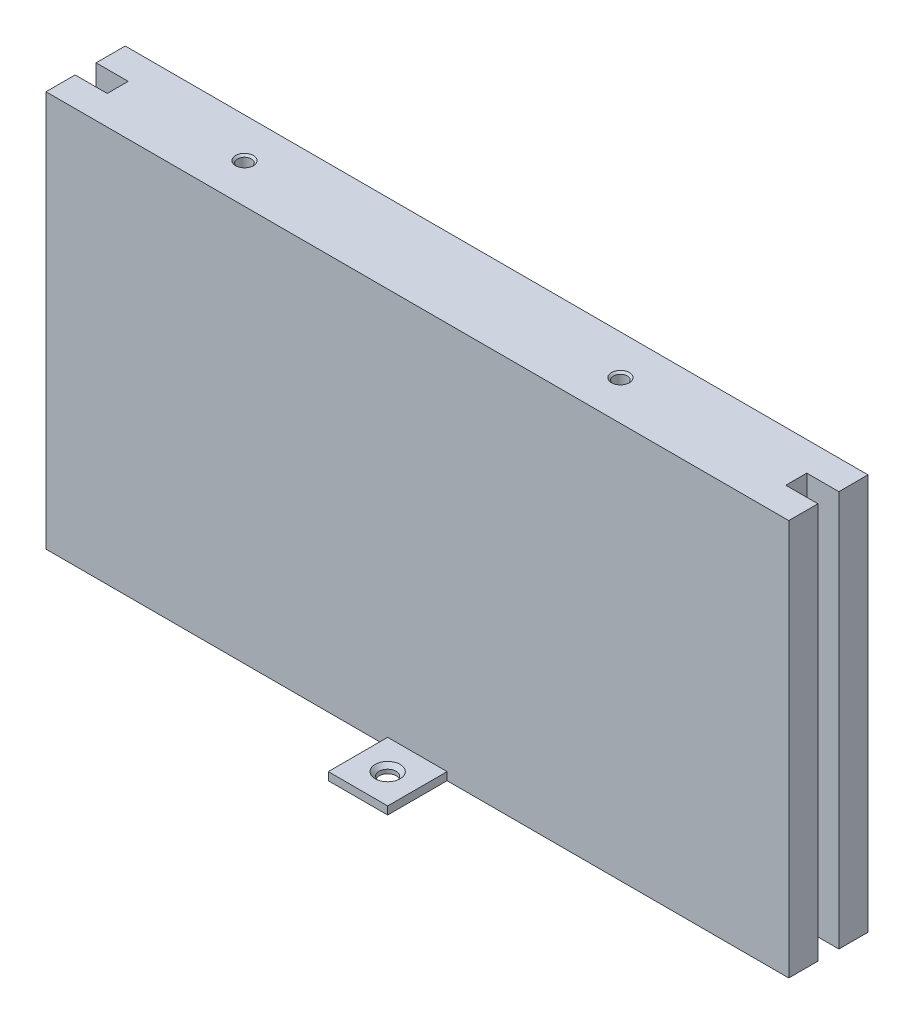
SolidWorks part; units mm, degrees
ref_plane "Front Plane" through (0, 0, 0) normal (0, 0, 1) x (1, 0, 0)
ref_plane "Top Plane" through (0, 0, 0) normal (0, 1, 0) x (1, 0, 0)
ref_plane "Right Plane" through (0, 0, 0) normal (1, 0, 0) x (0, 0, -1)
sketch "Sketch1" plane through (0, 0, 0) normal (0, 1, 0) x (1, 0, 0)
  line L0 (0, 0) -> (0, 20)
  line L1 (0, 20) -> (187.5, 20)
  line L2 (187.5, 20) -> (187.5, 0)
  line L3 (187.5, 0) -> (0, 0)
extrude "Boss-Extrude1" add sketch "Sketch1" along normal blind 100
sketch "Sketch2" plane through (0, 100, 0) normal (0, 1, 0) x (1, 0, 0)
  line L0 (0, 12.65) -> (8.1, 12.65)
  line L1 (0, 20) -> (0, 0) construction
  line L2 (8.1, 12.65) -> (8.1, 7.35)
  line L3 (0, 7.35) -> (0, 12.65)
  line L4 (0, 7.35) -> (8.1, 7.35)
  line L5 (0, 0) -> (187.5, 0) construction
  line L6 (187.5, 12.65) -> (179.4, 12.65)
  line L7 (187.5, 0) -> (187.5, 20) construction
  line L8 (179.4, 12.65) -> (179.4, 7.35)
  line L9 (179.4, 7.35) -> (187.5, 7.35)
  line L10 (187.5, 7.35) -> (187.5, 12.65)
  dimension "D1" = 5.3
  dimension "D2" = 8.1
  dimension "D3" = 7.35
  dimension "D4" = 8.1
  dimension "D5" = 7.35
extrude "Cut-Extrude1" cut sketch "Sketch2" against normal blind 100
sketch "Sketch3" plane through (0, 100, 0) normal (0, 1, 0) x (1, 0, 0)
  line L1 (187.5, 20) -> (0, 20) construction
  line L2 (187.5, 12.65) -> (187.5, 20) construction
  circle A0 centre (40.1, 10) radius 1.75
  circle A1 centre (135, 10) radius 1.75
  dimension "D1" = 3.5
  dimension "D4" = 3.5
  dimension "D6" = 10
  dimension "D2" = 52.5
  dimension "D3" = 10
  dimension "D5" = 94.9
extrude "Cut-Extrude2" cut sketch "Sketch3" against normal blind 8
chamfer "Chamfer1" distance 0.5 angle 45 1 edges at (40.1, 100, -8.25)
chamfer "Chamfer2" distance 0.5 angle 45 1 edges at (135, 100, -8.25)
sketch "Sketch4" plane through (0, 0, -20) normal (0, 0, -1) x (-1, 0, 0)
  line L0 (-101.25, 2) -> (-86.25, 2)
  line L1 (-86.25, 2) -> (-86.25, 0)
  line L2 (-187.5, 0) -> (0, 0) construction
  line L3 (-101.25, 2) -> (-101.25, 0)
  line L4 (0, 100) -> (0, 0) construction
  line L6 (-101.25, 0) -> (-86.25, 0)
  dimension "D1" = 15
  dimension "D2" = 86.25
  dimension "D3" = 2
extrude "Boss-Extrude2" add sketch "Sketch4" along normal blind 15
sketch "Sketch5" plane through (0, 0, 0) normal (0, 0, 1) x (1, 0, 0)
  line L0 (86.25, 0) -> (86.25, 2)
  line L1 (0, 0) -> (187.5, 0) construction
  line L2 (86.25, 2) -> (101.25, 2)
  line L3 (101.25, 2) -> (101.25, 0)
  line L4 (101.25, 0) -> (86.25, 0)
  line L5 (0, 100) -> (0, 0) construction
  dimension "D1" = 15
  dimension "D2" = 86.25
  dimension "D3" = 2
extrude "Boss-Extrude3" add sketch "Sketch5" along normal blind 15
sketch "Sketch6" plane through (0, 2, 0) normal (0, 1, 0) x (1, 0, 0)
  line L0 (101.25, 35) -> (101.25, 20) construction
  line L1 (86.25, 35) -> (101.25, 35) construction
  line L2 (101.25, -15) -> (101.25, 0) construction
  line L3 (101.25, -15) -> (86.25, -15) construction
  circle A0 centre (93.75, 27.5) radius 2.15
  circle A1 centre (93.75, -7.5) radius 2.15
  point P12 (95.4599, -15.5733)
  dimension "D1" = 4.3
  dimension "D6" = 4.3
  dimension "D2" = 7.5
  dimension "D3" = 7.5
  dimension "D4" = 7.5
  dimension "D5" = 7.5
extrude "Cut-Extrude3" cut sketch "Sketch6" against normal blind 15
chamfer "Chamfer3" distance 1 angle 45 2 edges at (91.6, 2, 7.5) (91.6, 2, -27.5)
